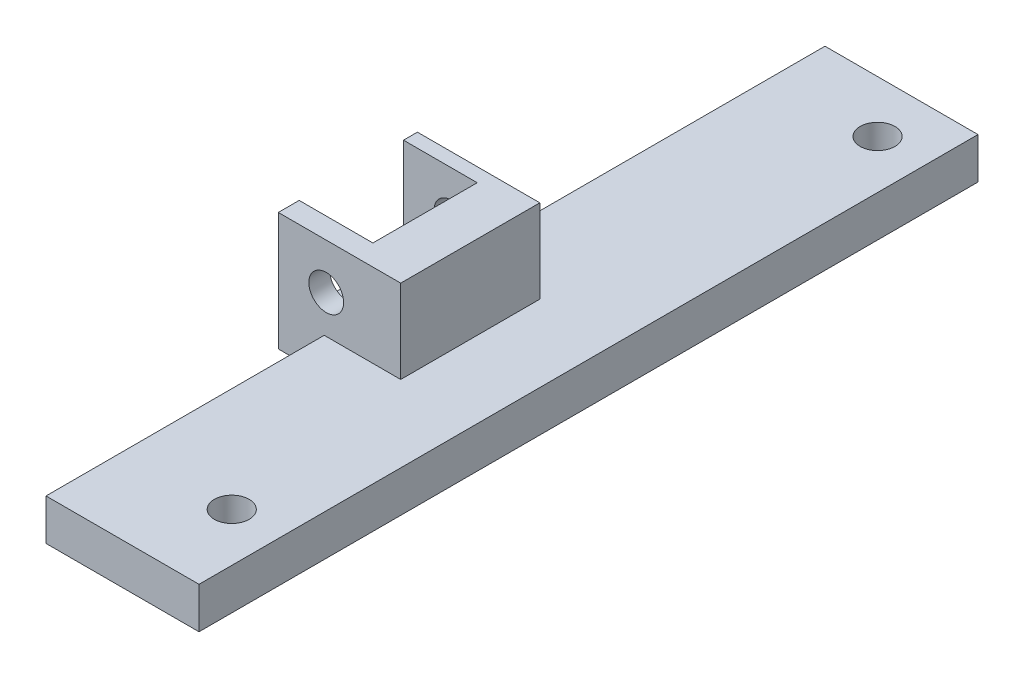
SolidWorks part; units mm, degrees
ref_plane "Front Plane" through (0, 0, 0) normal (0, 0, 1) x (1, 0, 0)
ref_plane "Top Plane" through (0, 0, 0) normal (0, 1, 0) x (1, 0, 0)
ref_plane "Right Plane" through (0, 0, 0) normal (1, 0, 0) x (0, 0, -1)
sketch "Sketch1" plane through (0, 0, 0) normal (0, 0, 1) x (1, 0, 0)
  line L0 (792.5838, 113.9662) -> (792.5838, 92.3762)
  line L1 (806.0458, 113.9662) -> (775.9383, 113.9662) construction
  line L2 (792.5838, 92.3762) -> (814.9358, 92.3762)
  line L3 (814.9358, 92.3762) -> (814.9358, 113.9662)
  line L4 (814.9358, 113.9662) -> (792.5838, 113.9662)
  line L5 (792.5838, 96.1608) -> (801.3383, 96.1608)
  line L6 (801.3383, 96.1608) -> (791.1783, 96.1608) construction
  circle A0 centre (801.3383, 105.6858) radius 3.175
  arc A1 (801.3383, 96.1608) -> (806.0458, 97.4054) centre (801.3383, 105.6858) ccw construction
  arc A2 (801.3383, 96.1608) -> (806.0458, 97.4054) centre (801.3383, 105.6858) ccw
  arc A3 (806.0458, 97.4054) -> (806.0458, 113.9662) centre (801.3383, 105.6858) ccw
  dimension "D1" = 6.35
  dimension "D2" = 22.352
  dimension "D3" = 21.59
  dimension "D4" = 8.89
extrude "Boss-Extrude1" add sketch "Sketch1" against normal blind 21.59 contours A3 A2 L5 L0 L2 L3 L4
sketch "Sketch2" plane through (0, 0, 0) normal (0, 0, 1) x (1, 0, 0)
  line L1 (792.5838, 92.3762) -> (814.9358, 92.3762)
  line L2 (792.5838, 92.3762) -> (792.5838, 113.9662)
  line L3 (792.5838, 113.9662) -> (814.9358, 113.9662)
  line L4 (814.9358, 92.3762) -> (814.9358, 113.9662)
  circle A0 centre (801.3383, 105.6858) radius 3.175
  dimension "D1" = 6.35
extrude "Boss-Extrude2" add sketch "Sketch2" along normal blind 3.81
sketch "Sketch3" plane through (0, 0, -21.59) normal (0, 0, -1) x (-1, 0, 0)
  line L0 (-792.5838, 96.1608) -> (-801.3383, 96.1608)
  line L1 (-814.9358, 92.3762) -> (-792.5838, 92.3762)
  line L2 (-814.9358, 92.3762) -> (-814.9358, 113.9662)
  line L3 (-814.9358, 113.9662) -> (-792.5838, 113.9662)
  line L4 (-792.5838, 92.3762) -> (-792.5838, 113.9662)
  circle A0 centre (-801.3383, 105.6858) radius 3.175
  arc A1 (-801.3383, 96.1608) -> (-806.0458, 113.9662) centre (-801.3383, 105.6858) cw
  arc M6 (-801.3383, 96.1608) -> (-806.0458, 113.9662) centre (-801.3383, 105.6858) cw
  line M11 (-792.5838, 96.1608) -> (-801.3383, 96.1608)
  dimension "D3" = 6.35
  dimension "D1" = 21.59
  dimension "D2" = 22.352
extrude "Boss-Extrude3" add sketch "Sketch3" against normal up to surface (2.54 mm away) contours L4 L3 A0 M11 M6
sketch "Sketch4" plane through (0, 92.3762, 0) normal (0, -1, 0) x (1, 0, 0)
  line L0 (800.9658, 54.61) -> (800.9658, -87.63)
  line L1 (800.9658, -87.63) -> (828.9058, -87.63)
  line L2 (828.9058, -87.63) -> (828.9058, 54.61)
  line L3 (828.9058, 54.61) -> (800.9658, 54.61)
  circle A0 centre (820.039, 39.7686) radius 3.175
  circle A1 centre (820.039, -78.16) radius 3.175
  dimension "D1" = 6.35
  dimension "D2" = 6.35
extrude "Boss-Extrude4" add sketch "Sketch4" along normal up to surface (1.1648 mm away) and the other way blind 6.35
